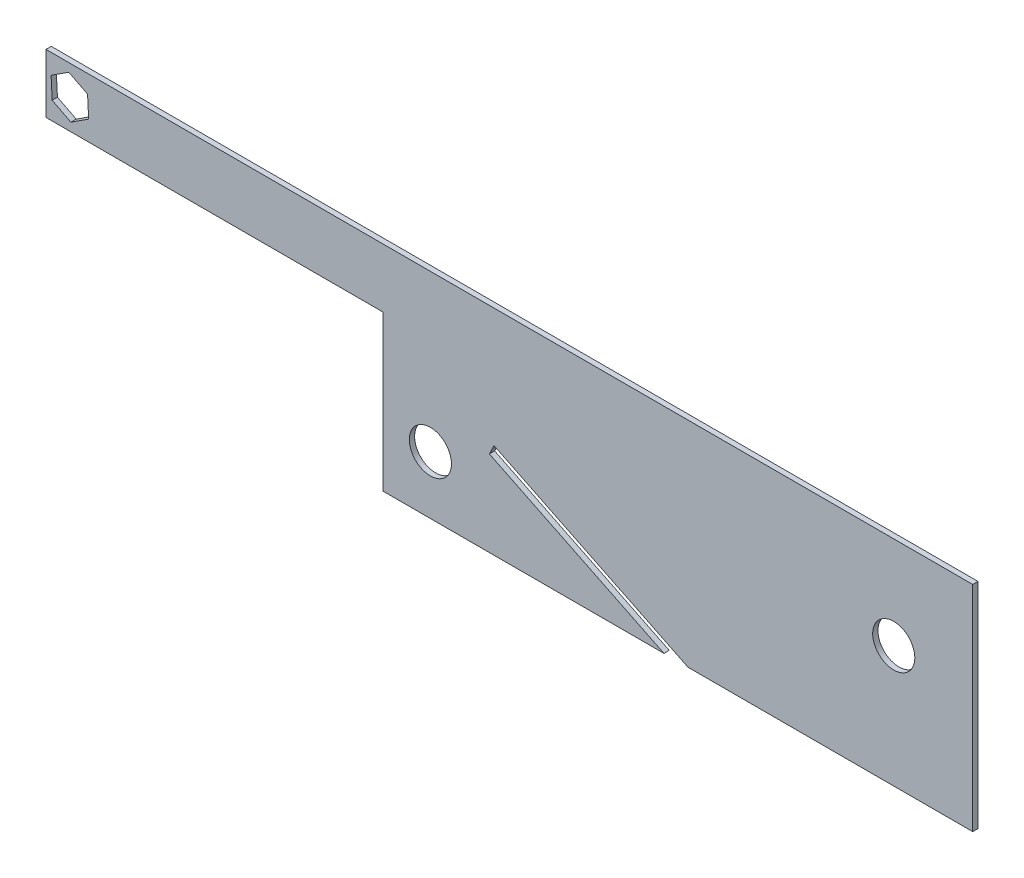
SolidWorks part; units mm, degrees
ref_plane "Front Plane" through (0, 0, 0) normal (0, 0, 1) x (1, 0, 0)
ref_plane "Top Plane" through (0, 0, 0) normal (0, 1, 0) x (1, 0, 0)
ref_plane "Right Plane" through (0, 0, 0) normal (1, 0, 0) x (0, 0, -1)
sketch "Sketch5" plane through (0, 0, 0) normal (0, 0, 1) x (1, 0, 0)
  line L0 (0, 0) -> (203.2, 0)
  line L1 (203.2, 0) -> (203.2, -93.5339)
  line L2 (0, 0) -> (0, 35.56)
  line L3 (0, 35.56) -> (558.8, 35.56)
  line L4 (558.8, 35.56) -> (558.8, -93.5339)
  line L5 (558.8, -93.5339) -> (203.2, -93.5339)
  line L6 (372.6374, -93.5339) -> (267.3456, -42.0146)
  line L7 (267.3456, -42.0146) -> (270.1365, -36.3108)
  line L8 (270.1365, -36.3108) -> (387.0853, -93.5339)
  line L10 (25.7114, 11.9913) -> (25.0633, 24.6913)
  line L11 (25.0633, 24.6913) -> (13.7407, 30.48)
  line L12 (13.7407, 30.48) -> (3.0662, 23.5687)
  line L13 (3.0662, 23.5687) -> (3.7143, 10.8687)
  line L14 (3.7143, 10.8687) -> (15.0369, 5.08)
  line L15 (15.0369, 5.08) -> (25.7114, 11.9913)
  circle A0 centre (511.175, -20.2483) radius 12.7
  circle A1 centre (231.775, -58.6089) radius 12.7
  circle A4 centre (14.3888, 17.78) radius 11.0128 construction
  dimension "D1" = 279.4
  dimension "D3" = 25.4
  dimension "D4" = 28.575
  dimension "D2" = 558.8
  dimension "D7" = 6.35
  dimension "D8" = 5.08
  dimension "D9" = 5.08
  dimension "D10" = 25.4
extrude "Boss-Extrude4" add sketch "Sketch5" along normal blind 3.175 contours L7 L8 L5 L4 L3 L2 L0 L1 L6 A1 A0 L15 L14 L13 L12 L11 L10
